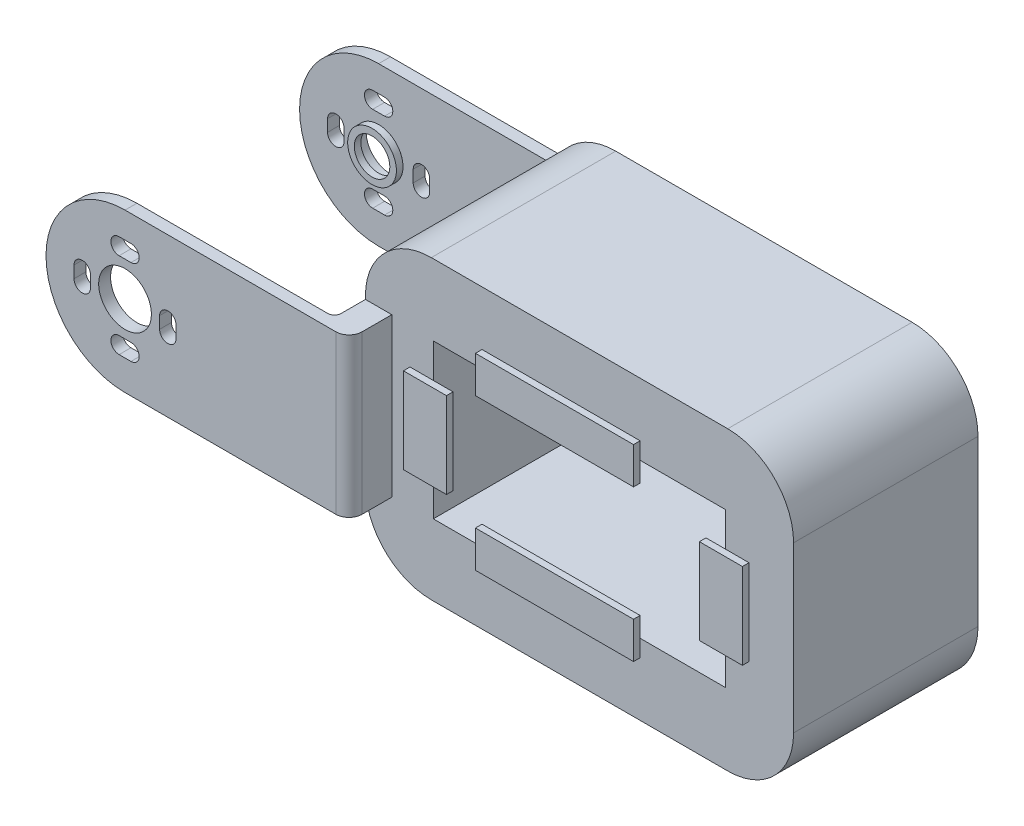
SolidWorks part; units mm, degrees
ref_plane "前基準面" through (0, 0, 0) normal (0, 0, 1) x (1, 0, 0)
ref_plane "上基準面" through (0, 0, 0) normal (0, 1, 0) x (1, 0, 0)
ref_plane "右基準面" through (0, 0, 0) normal (1, 0, 0) x (0, 0, -1)
sketch "草圖1" plane through (0, 0, 0) normal (0, 0, 1) x (1, 0, 0)
  line L0 (-9.02, 0) -> (7.9922, 0) construction
  line L2 (-59.9347, 22.5) -> (5.0653, 22.5)
  line L3 (-59.9347, 22.5) -> (-59.9347, -22.5)
  line L4 (-59.9347, -22.5) -> (5.0653, -22.5)
  line L5 (5.0653, 22.5) -> (5.0653, -22.5)
  dimension "D1" = 45
  dimension "D2" = 22.5
  dimension "D3" = 65
extrude "填料-伸長1" add sketch "草圖1" along normal blind 28
sketch "草圖2" plane through (0, 0, 0) normal (0, 0, 1) x (1, 0, 0)
  line L0 (-59.9347, 0) -> (5.361, 0) construction
  line L1 (-59.9347, 22.5) -> (-59.9347, -22.5) construction
  line L2 (-27.4347, 22.5) -> (-27.4347, -22.5) construction
  line L3 (5.0653, 22.5) -> (-59.9347, 22.5) construction
  line L4 (-59.9347, -22.5) -> (5.0653, -22.5) construction
  line L6 (-49.6347, 11.7) -> (-5.2347, 11.7)
  line L7 (-49.6347, 11.7) -> (-49.6347, -11.7)
  line L8 (-49.6347, -11.7) -> (-5.2347, -11.7)
  line L9 (-5.2347, 11.7) -> (-5.2347, -11.7)
  dimension "D1" = 44.4
  dimension "D2" = 23.4
  dimension "D3" = 10.3
  dimension "D4" = 10.8
extrude "除料-伸長1" cut sketch "草圖2" along normal blind 39
ref_plane "平面1" through (0, 0, 28) normal (0, 0, 1) x (1, 0, 0)
sketch "草圖3" plane through (0, 0, 28) normal (0, 0, 1) x (1, 0, 0)
  line L0 (-59.9347, 22.5) -> (-59.9347, -22.5) construction
  line L2 (-59.9347, 12) -> (-55.9347, 12)
  line L3 (-59.9347, 12) -> (-59.9347, -12)
  line L4 (-59.9347, -12) -> (-55.9347, -12)
  line L5 (-55.9347, 12) -> (-55.9347, -12)
  line L8 (-5.2347, -11.7) -> (-49.6347, -11.7) construction
  dimension "D1" = 4
  dimension "D2" = 24
  dimension "D3" = 0.3
extrude "填料-伸長2" add sketch "草圖3" along normal blind 6
ref_plane "平面2" through (-59.9347, 0, 0) normal (-1, 0, 0) x (0, 0, 1)
sketch "草圖4" plane through (-59.9347, 0, 0) normal (-1, 0, 0) x (0, 0, 1)
  line L0 (34, 12) -> (28, 12) construction
  line L2 (32, 12) -> (34, 12)
  line L3 (32, 12) -> (32, -12)
  line L4 (32, -12) -> (34, -12)
  line L5 (34, 12) -> (34, -12)
  dimension "D1" = 2
ref_plane "平面3" through (0, 0, 33) normal (0, 0, 1) x (1, 0, 0)
sketch "草圖6" plane through (0, 0, 28) normal (0, 0, 1) x (1, 0, 0)
  line L0 (-15.2347, 0.3) -> (5.0653, -22.5)
  line L1 (-5.2347, 11.7) -> (-5.2347, -11.7) construction
  line L2 (-5.2347, -11.7) -> (-49.6347, -11.7) construction
  line L3 (-15.2347, 0.3) -> (-15.2347, -22.5)
  line L4 (-59.9347, -22.5) -> (5.0653, -22.5) construction
  line L5 (-15.2347, -22.5) -> (5.0653, -22.5)
  dimension "D1" = 10
  dimension "D2" = 12
sketch "草圖7" plane through (0, 0, 33) normal (0, 0, 1) x (1, 0, 0)
  line L1 (-59.9347, 12) -> (-59.9347, -12) construction
  line L3 (-59.9347, 0) -> (-109.9347, 0) construction
  line L5 (-96.4347, 0.9) -> (-96.4347, -0.9) construction
  line L6 (-95.1847, 0.9) -> (-95.1847, -0.9)
  line L7 (-97.6847, 0.9) -> (-97.6847, -0.9)
  line L8 (-90.8347, -6.2) -> (-89.0347, -6.2) construction
  line L9 (-90.8347, -4.95) -> (-89.0347, -4.95)
  line L10 (-90.8347, -7.45) -> (-89.0347, -7.45)
  line L11 (-89.9347, 4.3) -> (-89.9347, -7.9506) construction
  line L12 (-90.8347, 6.8) -> (-89.0347, 6.8) construction
  line L13 (-90.8347, 5.55) -> (-89.0347, 5.55)
  line L14 (-90.8347, 8.05) -> (-89.0347, 8.05)
  line L15 (-83.4347, 0.75) -> (-83.4347, -1.05) construction
  line L16 (-84.6847, 0.75) -> (-84.6847, -1.05)
  line L17 (-82.1847, 0.75) -> (-82.1847, -1.05)
  line L19 (-59.9347, 12) -> (-59.9347, -12)
  line L20 (-59.9347, -12) -> (-89.9347, -12)
  line L21 (-59.9347, 12) -> (-89.9347, 12)
  circle A1 centre (-89.9347, 0.3) radius 4
  arc A3 (-95.1847, 0.9) -> (-97.6847, 0.9) centre (-96.4347, 0.9) ccw
  arc A4 (-97.6847, -0.9) -> (-95.1847, -0.9) centre (-96.4347, -0.9) ccw
  arc A5 (-90.8347, -4.95) -> (-90.8347, -7.45) centre (-90.8347, -6.2) ccw
  arc A6 (-89.0347, -7.45) -> (-89.0347, -4.95) centre (-89.0347, -6.2) ccw
  arc A7 (-90.8347, 5.55) -> (-90.8347, 8.05) centre (-90.8347, 6.8) cw
  arc A8 (-89.0347, 8.05) -> (-89.0347, 5.55) centre (-89.0347, 6.8) cw
  arc A9 (-84.6847, 0.75) -> (-82.1847, 0.75) centre (-83.4347, 0.75) cw
  arc A10 (-82.1847, -1.05) -> (-84.6847, -1.05) centre (-83.4347, -1.05) cw
  arc A11 (-89.9347, 12) -> (-89.9347, -12) centre (-89.9347, 0) ccw
  point P15 (-96.4347, 0)
  point P20 (-89.9347, -6.2)
  point P31 (-89.9347, 6.8)
  point P38 (-83.4347, -0.15)
  dimension "D2" = 8
  dimension "D3" = 50
  dimension "D4" = 6.5
  dimension "D6" = 0
  dimension "D5" = 1.8
  dimension "D7" = 2.5
  dimension "D8" = 2.5
  dimension "D9" = 0
  dimension "D10" = 1.8
  dimension "D11" = 6.5
  dimension "D12" = 6.5
  dimension "D13" = 6.5
  dimension "D14" = 1.8
  dimension "D15" = 2.5
  dimension "D16" = 1.8
  dimension "D17" = 2.5
extrude "填料-伸長3" add sketch "草圖7" along normal blind 1.5 and the other way blind 0.3
ref_plane "平面4" through (0, 0, 0) normal (0, 0, -1) x (-1, 0, 0)
sketch "草圖8" plane through (0, 0, 0) normal (0, 0, -1) x (-1, 0, 0)
  line L0 (59.9347, 12) -> (59.9347, -12) construction
  line L1 (55.9347, 12) -> (59.9347, 12)
  line L2 (55.9347, 12) -> (55.9347, -12)
  line L3 (55.9347, -12) -> (59.9347, -12)
  line L4 (59.9347, 12) -> (59.9347, -12)
  dimension "D1" = 24
  dimension "D2" = 4
extrude "填料-伸長4" add sketch "草圖8" along normal blind 6 contours L3 L4 L1 L2
fillet "圓角1" radius 10 1 edges at (-59.9347, -22.5, 14)
fillet "圓角2" radius 10 1 edges at (-59.9347, 22.5, 14)
fillet "圓角3" radius 10 1 edges at (5.0653, 22.5, 14)
fillet "圓角4" radius 10 1 edges at (5.0653, -22.5, 14)
pattern_linear "直線複製排列2" count 2 spacing 38.5 along (0, 0, -1) of "填料-伸長3"
fillet "圓角5" radius 2 1 edges at (-55.9347, 0, -6)
ref_plane "平面5" through (0, 0, -4) normal (0, 0, 1) x (1, 0, 0)
sketch "草圖9" plane through (0, 0, -4) normal (0, 0, 1) x (1, 0, 0)
  circle A0 centre (-89.9347, 0.3) radius 3.7
  circle A1 centre (-89.9347, 0.3) radius 2.7
  dimension "D1" = 7.4
  dimension "D2" = 5.4
extrude "填料-伸長5" add sketch "草圖9" along normal blind 1 separate body
ref_plane "平面6" through (0, 0, 29) normal (0, 0, 1) x (1, 0, 0)
sketch "草圖10" plane through (0, 0, 29) normal (0, 0, 1) x (1, 0, 0)
  line L0 (-49.6347, 11.7) -> (-5.2347, 11.7) construction
  line L2 (-42.2347, 11.7) -> (-42.2347, 14.2663)
  line L3 (-42.2347, 14.2663) -> (-18.2347, 14.2663)
  line L4 (-18.2347, 11.7) -> (-18.2347, 14.2663)
  line L5 (-5.2347, 11.7) -> (-5.2347, -11.7) construction
  line L6 (-49.6347, 0) -> (-4.2092, 0) construction
  line L7 (-49.6347, -11.7) -> (-49.6347, 11.7) construction
  line L8 (-27.4347, -11.7) -> (-27.4347, 19.297) construction
  line L9 (-5.2347, -11.7) -> (-49.6347, -11.7) construction
  line L10 (-42.2347, 11.7) -> (-42.2347, 8.7)
  line L11 (-49.6347, 6.5) -> (-53.1651, 6.5)
  line L13 (-49.6347, -6.5) -> (-53.1651, -6.5)
  line L14 (-53.1651, 6.5) -> (-53.1651, -6.5)
  line L15 (-42.2347, 8.7) -> (-18.2347, 8.7)
  line L16 (-18.2347, 8.7) -> (-18.2347, 11.7)
  line L17 (-49.6347, 6.5) -> (-46.6347, 6.5)
  line L18 (-46.6347, 6.5) -> (-46.6347, -6.5)
  line L19 (-46.6347, -6.5) -> (-49.6347, -6.5)
  line L20 (-42.2347, -11.7) -> (-42.2347, -8.7)
  line L21 (-42.2347, -8.7) -> (-18.2347, -8.7)
  line L22 (-18.2347, -8.7) -> (-18.2347, -11.7)
  line L23 (-18.2347, -11.7) -> (-18.2347, -14.2663)
  line L24 (-42.2347, -14.2663) -> (-18.2347, -14.2663)
  line L25 (-42.2347, -11.7) -> (-42.2347, -14.2663)
  line L26 (-5.2347, 6.5) -> (-8.2347, 6.5)
  line L27 (-8.2347, 6.5) -> (-8.2347, -6.5)
  line L28 (-8.2347, -6.5) -> (-5.2347, -6.5)
  line L29 (-5.2347, -6.5) -> (-1.7043, -6.5)
  line L30 (-1.7043, 6.5) -> (-1.7043, -6.5)
  line L31 (-5.2347, 6.5) -> (-1.7043, 6.5)
  point P6 (-18.2347, 12.9831)
  dimension "D1" = 24
  dimension "D2" = 13
  dimension "D3" = 13
  dimension "D4" = 6.5
  dimension "D5" = 3
  dimension "D6" = 3
extrude "填料-伸長6" add sketch "草圖10" against normal blind 1 separate body
ref_plane "平面7" through (0, 0, -4) normal (0, 0, -1) x (-1, 0, 0)
sketch "草圖12" plane through (0, 0, -4) normal (0, 0, -1) x (-1, 0, 0)
  circle A0 centre (89.9347, 0.3) radius 4
  circle A1 centre (89.9347, 0.3) radius 3.7
extrude "填料-伸長8" add sketch "草圖12" along normal blind 1.8
ref_plane "平面9" through (0, 0, 34) normal (0, 0, 1) x (1, 0, 0)
sketch "草圖15" plane through (0, 0, 34) normal (0, 0, 1) x (1, 0, 0)
  line L0 (-59.9347, 12) -> (-59.9347, -12) construction
  line L1 (-59.9347, 12) -> (-55.9347, 12)
  line L2 (-59.9347, 12) -> (-59.9347, -12)
  line L3 (-59.9347, -12) -> (-55.9347, -12)
  line L4 (-55.9347, 12) -> (-55.9347, -12)
  line L5 (-55.9347, 12) -> (-59.9347, 12) construction
  dimension "D1" = 24
  dimension "D2" = 4
extrude "填料-伸長10" add sketch "草圖15" along normal blind 0.5
fillet "圓角16" radius 2 1 edges at (-55.9347, 0, 34.5)
fillet "圓角17" radius 1 1 edges at (-59.9347, 0, 32.7)
fillet "圓角18" radius 1 1 edges at (-59.9347, 0, -4)
